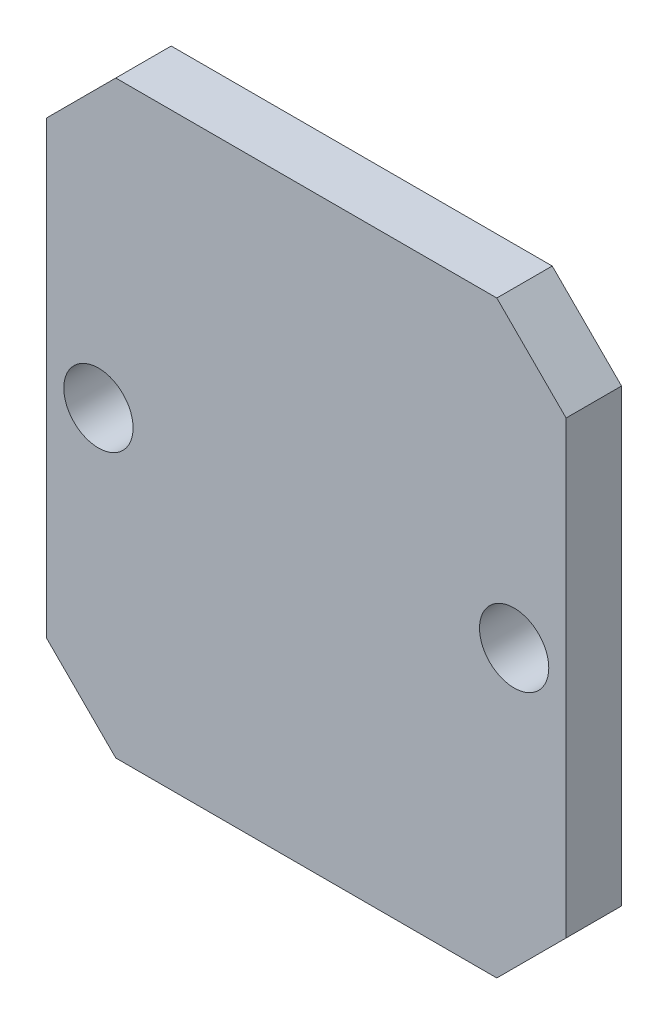
SolidWorks part; units mm, degrees
ref_plane "Plano frontal" through (0, 0, 0) normal (0, 0, 1) x (1, 0, 0)
ref_plane "Plano superior" through (0, 0, 0) normal (0, 1, 0) x (1, 0, 0)
ref_plane "Plano direito" through (0, 0, 0) normal (1, 0, 0) x (0, 0, -1)
sketch "Esboço1" plane through (0, 0, 0) normal (0, 0, 1) x (1, 0, 0)
  line L1 (-4.6046, 4.8) -> (10.3954, 4.8)
  line L2 (-4.6046, 4.8) -> (-4.6046, -12.2)
  line L3 (-4.6046, -12.2) -> (10.3954, -12.2)
  line L4 (10.3954, 4.8) -> (10.3954, -12.2)
  circle A0 centre (8.8954, -3.7) radius 1
  circle A1 centre (-3.1046, -3.7) radius 1
  dimension "D3" = 2
  dimension "D4" = 2
  dimension "D1" = 15
  dimension "D2" = 17
extrude "Ressalto-extrusão1" add sketch "Esboço1" along normal blind 1.6
chamfer "Chanfro1" distance 2 angle 45 4 edges at (-4.6046, -12.2, 0.8) (10.3954, -12.2, 0.8) (-4.6046, 4.8, 0.8) (10.3954, 4.8, 0.8)
